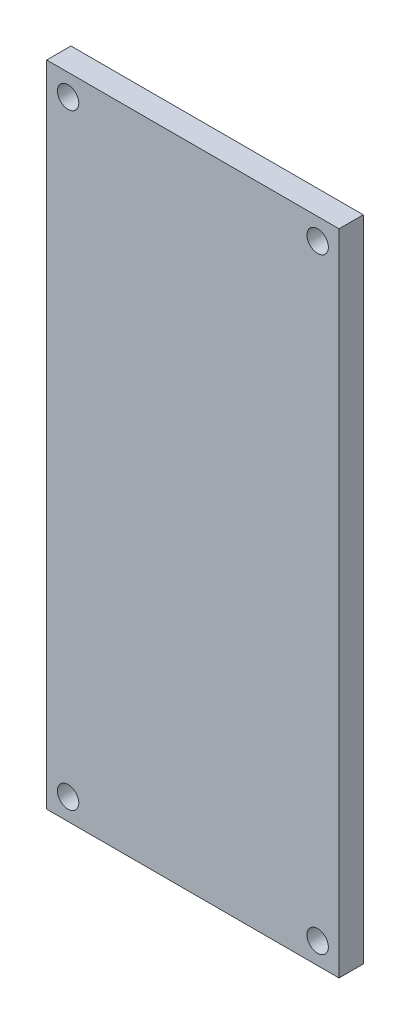
SolidWorks part; units mm, degrees
ref_plane "Front Plane" through (0, 0, 0) normal (0, 0, 1) x (1, 0, 0)
ref_plane "Top Plane" through (0, 0, 0) normal (0, 1, 0) x (1, 0, 0)
ref_plane "Right Plane" through (0, 0, 0) normal (1, 0, 0) x (0, 0, -1)
sketch "Sketch1" plane through (0, 0, 0) normal (0, 0, 1) x (1, 0, 0)
  line L0 (10.25, 0) -> (-10.25, 0) construction
  line L1 (-10.25, 22.75) -> (10.25, 22.75)
  line L2 (-10.25, 22.75) -> (-10.25, -22.75)
  line L3 (-10.25, -22.75) -> (10.25, -22.75)
  line L4 (10.25, 22.75) -> (10.25, -22.75)
  dimension "D1" = 20.5
  dimension "D2" = 45.5
extrude "Extrude1" add sketch "Sketch1" along normal blind 1.7
sketch "Sketch2" plane through (0, 0, 1.7) normal (0, 0, 1) x (1, 0, 0)
  line L4 (0, 0) -> (0, -22.75) construction
  line L5 (-10.25, -22.75) -> (10.25, -22.75) construction
  line L12 (0, 0) -> (-10.25, 0) construction
  line L13 (-10.25, 22.75) -> (-10.25, -22.75) construction
  circle A0 centre (8.75, -21.25) radius 0.75
  circle A1 centre (-8.75, -21.25) radius 0.75
  circle A2 centre (-8.75, 21.25) radius 0.75
  circle A3 centre (8.75, 21.25) radius 0.75
  point P17 (-0.2474, 0.2312)
  dimension "D1" = 1.5
  dimension "D2" = 21.25
  dimension "D3" = 8.75
extrude "Cut-Extrude1" cut sketch "Sketch2" against normal up to surface (1.7 mm away) up to face at (0, 0, 0)
